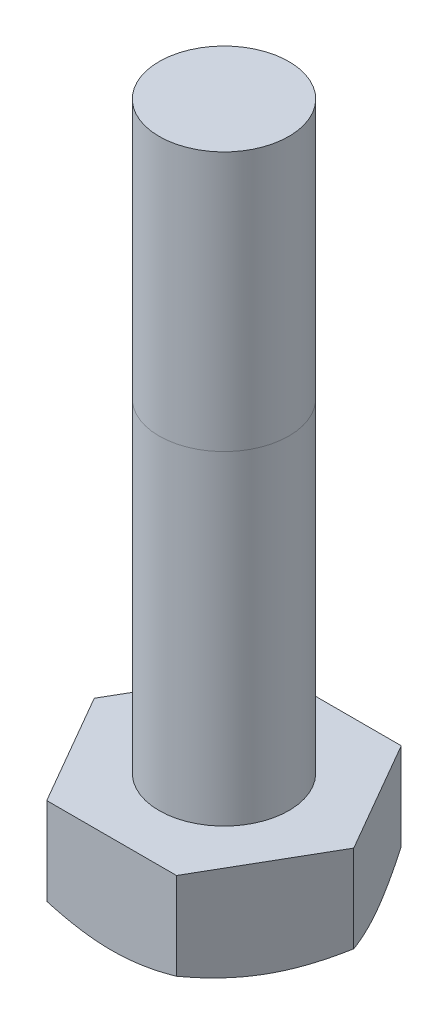
SolidWorks part; units mm, degrees
ref_plane "Front Plane" through (0, 0, 0) normal (0, 0, 1) x (1, 0, 0)
ref_plane "Top Plane" through (0, 0, 0) normal (0, 1, 0) x (1, 0, 0)
ref_plane "Right Plane" through (0, 0, 0) normal (1, 0, 0) x (0, 0, -1)
sketch "Sketch1" plane through (0, 0, 0) normal (0, 1, 0) x (1, 0, 0)
  line L1 (20, 0) -> (10, 17.3205)
  line L2 (10, 17.3205) -> (-10, 17.3205)
  line L3 (-10, 17.3205) -> (-20, 0)
  line L4 (-20, 0) -> (-10, -17.3205)
  line L5 (-10, -17.3205) -> (10, -17.3205)
  line L6 (10, -17.3205) -> (20, 0)
  circle A0 centre (0, 0) radius 17.3205 construction
  dimension "D1" = 20
extrude "Boss-Extrude1" add sketch "Sketch1" along normal blind 15
sketch "Sketch2" plane through (0, 15, 0) normal (0, 1, 0) x (1, 0, 0)
  circle A0 centre (0, 0) radius 10
  dimension "D1" = 20
extrude "Boss-Extrude2" add sketch "Sketch2" along normal blind 90
sketch "Sketch3" plane through (0, 0, 0) normal (0, -1, 0) x (1, 0, 0)
  circle A0 centre (0, 0) radius 17.3205
extrude "Cut-Extrude1" cut sketch "Sketch3" against normal blind 90 draft 60 flip side to cut
sketch "Sketch5" plane through (0, 0, 0) normal (1, 0, 0) x (0, 0, -1)
  line L0 (-10, 65) -> (10, 65)
  line L1 (-10, 105) -> (-10, 15) construction
  line L2 (10, 15) -> (10, 105) construction
  line L3 (10, 105) -> (-10, 105) construction
  dimension "D1" = 40
split line "Split Line1"
sketch "Sketch7" plane through (0, 105, 0) normal (0, 1, 0) x (1, 0, 0)
  circle A0 centre (0, 0) radius 10
curve "Helix/Spiral1" pitch 1 height 40 turns 40
